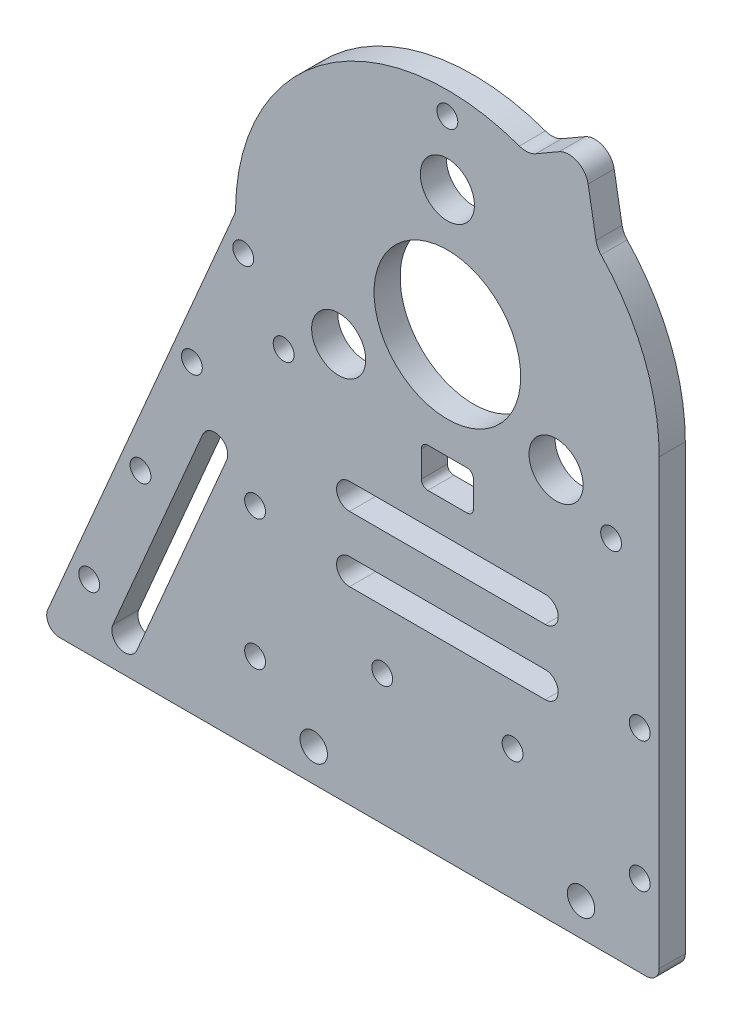
SolidWorks part; units mm, degrees
material "Thornel Mat VMA"
ref_plane "前视" through (0, 0, 0) normal (0, 0, 1) x (1, 0, 0)
ref_plane "上视" through (0, 0, 0) normal (0, 1, 0) x (1, 0, 0)
ref_plane "右视" through (0, 0, 0) normal (1, 0, 0) x (0, 0, -1)
sketch "草图1" plane through (0, 0, 0) normal (0, 0, 1) x (1, 0, 0)
  circle A0 centre (0, 0) radius 32.5
  circle A1 centre (0, 0) radius 11.25
  dimension "D1" = 22.5
  dimension "D2" = 65
extrude "凸台-拉伸1" add sketch "草图1" along normal blind 4
sketch "草图2" plane through (0, 0, 4) normal (0, 0, 1) x (1, 0, 0)
  line L0 (-32.5, 0) -> (-32.5, -70)
  line L1 (-32.5, -70) -> (32.5, -70)
  line L2 (32.5, -70) -> (32.5, 0)
  circle A0 centre (0, 0) radius 32.5 construction
  arc A1 (-32.5, 0) -> (32.5, 0) centre (0, 0) ccw
  dimension "D1" = 70
extrude "凸台-拉伸2" add sketch "草图2" against normal blind 4
sketch "草图3" plane through (0, 0, 4) normal (0, 0, 1) x (1, 0, 0)
  line L0 (0, 0) -> (0, 32.5) construction
  line L1 (0, 0) -> (0, 19.25) construction
  arc A0 (32.5, 0) -> (-32.5, 0) centre (0, 0) ccw construction
  circle A1 centre (0, 19.25) radius 4.15
  circle A2 centre (16.671, -9.625) radius 4.15
  circle A3 centre (-16.671, -9.625) radius 4.15
  dimension "D1" = 8.3
  dimension "D3" = 19.25
  dimension "D2" = 3
extrude "切除-拉伸1" cut sketch "草图3" against normal blind 4
sketch "草图4" plane through (0, 0, 4) normal (0, 0, 1) x (1, 0, 0)
  line L0 (0, 0) -> (0, 32.5) construction
  line L1 (0, 0) -> (0, 29) construction
  arc A0 (32.5, 0) -> (-32.5, 0) centre (0, 0) ccw construction
  circle A1 centre (0, 29) radius 1.6
  circle A2 centre (25.1147, -14.5) radius 1.6
  circle A3 centre (-25.1147, -14.5) radius 1.6
  dimension "D2" = 3.2
  dimension "D4" = 29
  dimension "D3" = 3
extrude "切除-拉伸2" cut sketch "草图4" against normal blind 4
sketch "草图5" plane through (0, 0, 4) normal (0, 0, 1) x (1, 0, 0)
  line L0 (0, 0) -> (0, -70) construction
  line L1 (-32.5, -70) -> (32.5, -70) construction
  line L2 (17.6, -70) -> (17.6, -74)
  line L3 (17.6, -70) -> (-17.6, -70)
  line L4 (0, -70) -> (0, -74)
  line L5 (17.6, -74) -> (-17.6, -74)
  line L6 (-17.6, -70) -> (-17.6, -74)
  line M14 (-32.5, -70) -> (32.5, -70)
  dimension "D1" = 4
  dimension "D2" = 17.6
extrude "凸台-拉伸3" add sketch "草图5" against normal blind 4 contours L6 L5 L4 M14 | L5 L2 L3 L4
sketch "草图6" plane through (0, 0, 4) normal (0, 0, 1) x (1, 0, 0)
  line L0 (0, 0) -> (0, -74) construction
  line L1 (17.6, -74) -> (-17.6, -74) construction
  line L2 (-32.5, -70) -> (-17.6, -70) construction
  line L3 (-20.5, -65) -> (20.5, -65) construction
  circle A0 centre (-20.5, -65) radius 2.1
  circle A1 centre (20.5, -65) radius 2.1
  dimension "D1" = 41
  dimension "D2" = 5
  dimension "D3" = 4.2
extrude "切除-拉伸3" cut sketch "草图6" against normal blind 4
sketch "草图7" plane through (0, 0, 4) normal (0, 0, 1) x (1, 0, 0)
  line L0 (0, 0) -> (0, -74) construction
  line L1 (17.6, -74) -> (-17.6, -74) construction
  line L3 (-4, -16.2) -> (4, -16.2)
  line L4 (-4, -16.2) -> (-4, -22.2)
  line L5 (-4, -22.2) -> (4, -22.2)
  line L6 (4, -16.2) -> (4, -22.2)
  line L7 (-4, -16.2) -> (4, -22.2) construction
  line L8 (-4, -22.2) -> (4, -16.2) construction
  point P5 (0, -19.2)
  dimension "D1" = 6
  dimension "D2" = 8
  dimension "D3" = 16.2
extrude "切除-拉伸4" cut sketch "草图7" against normal blind 4
fillet "圆角1" radius 1 4 edges at (4, -16.2, 2) (4, -22.2, 2) (-4, -22.2, 2) (-4, -16.2, 2)
sketch "草图8" plane through (0, 0, 0) normal (0, 0, -1) x (-1, 0, 0)
  line L0 (0, -74) -> (0, 0) construction
  line L1 (-17.6, -74) -> (17.6, -74) construction
  line L2 (-17.6, -70) -> (-32.5, -70) construction
  circle A0 centre (-10, -50) radius 1.6
  circle A1 centre (10, -50) radius 1.6
  dimension "D1" = 3.2
  dimension "D2" = 20
  dimension "D3" = 20
extrude "切除-拉伸5" cut sketch "草图8" against normal blind 10
sketch "草图9" plane through (0, 0, 4) normal (0, 0, 1) x (1, 0, 0)
  line L1 (-17.6, -74) -> (17.6, -74)
  line L2 (-17.6, -74) -> (-17.6, -70)
  line L3 (-17.6, -70) -> (17.6, -70)
  line L4 (17.6, -74) -> (17.6, -70)
extrude "切除-拉伸6" cut sketch "草图9" against normal blind 10
sketch "草图10" plane through (0, 0, 4) normal (0, 0, 1) x (1, 0, 0)
  line L0 (-29.5, -70) -> (-29.5, 44.9866) construction
  line L1 (-32.5, -70) -> (32.5, -70) construction
  line L2 (-32.5, 0) -> (-32.5, -70) construction
  line L3 (0, 32.5) -> (0, -70) construction
  circle A0 centre (-29.5, -57.5) radius 1.6
  circle A1 centre (-29.5, -37.5) radius 1.6
  arc A2 (32.5, 0) -> (-32.5, 0) centre (0, 0) ccw construction
  circle A3 centre (29.5, -37.5) radius 1.6
  circle A4 centre (29.5, -57.5) radius 1.6
  dimension "D2" = 3.2
  dimension "D3" = 12.5
  dimension "D4" = 20
  dimension "D1" = 3
extrude "切除-拉伸7" cut sketch "草图10" against normal blind 10
sketch "草图11" plane through (0, 0, 4) normal (0, 0, 1) x (1, 0, 0)
  line L0 (12.3168, 30.0757) -> (20.846, 35)
  line L1 (20.846, 35) -> (22.9619, 23)
  line L2 (-1000, 0) -> (49000, 0) construction
  arc A0 (32.5, 0) -> (-32.5, 0) centre (0, 0) ccw construction
  arc A1 (22.9619, 23) -> (12.3168, 30.0757) centre (0, 0) ccw
  dimension "D1" = 100
  dimension "D2" = 30
  dimension "D3" = 35
  dimension "D4" = 12
extrude "凸台-拉伸4" add sketch "草图11" against normal blind 4
fillet "圆角2" radius 3 3 edges at (12.3168, 30.0757, 2) (22.9619, 23, 2) (20.846, 35, 2)
sketch "草图12" plane through (0, 0, 4) normal (0, 0, 1) x (1, 0, 0)
  line L0 (-15, -29) -> (15, -29) construction
  line L1 (-15, -27) -> (15, -27)
  line L2 (-15, -31) -> (15, -31)
  line L3 (0, 0) -> (0, -29) construction
  line L4 (-15, -39) -> (15, -39) construction
  line L5 (-15, -37) -> (15, -37)
  line L6 (-15, -41) -> (15, -41)
  arc A0 (-15, -27) -> (-15, -31) centre (-15, -29) ccw
  arc A1 (15, -31) -> (15, -27) centre (15, -29) ccw
  circle A2 centre (0, 0) radius 11.25 construction
  arc A3 (-15, -37) -> (-15, -41) centre (-15, -39) ccw
  arc A4 (15, -41) -> (15, -37) centre (15, -39) ccw
  point P2 (0, -29)
  point P14 (0, -39)
  dimension "D2" = 2
  dimension "D4" = 2
  dimension "D1" = 30
  dimension "D3" = 27
  dimension "D5" = 30
  dimension "D6" = 6
extrude "切除-拉伸8" cut sketch "草图12" against normal blind 10
sketch "草图13" plane through (0, 0, 4) normal (0, 0, 1) x (1, 0, 0)
  line L0 (-32.5, 0) -> (-62.5, -70)
  line L1 (-62.5, -70) -> (-32.5, -70)
  line L2 (-32.5, -70) -> (-32.5, 0)
  line L3 (-32.5, -70) -> (32.5, -70) construction
  dimension "D1" = 30
extrude "凸台-拉伸5" add sketch "草图13" against normal blind 4
fillet "圆角3" radius 2 3 edges at (32.5, -70, 2) (-62.5, -70, 2) (-32.5, 0, 2)
sketch "草图14" plane through (0, 0, 4) normal (0, 0, 1) x (1, 0, 0)
  line L0 (-35.6903, -32.8299) -> (-49.4775, -65) construction
  line L1 (-33.852, -33.6178) -> (-47.6392, -65.7878)
  line L2 (-37.5286, -32.0421) -> (-51.3158, -64.2122)
  line L3 (-32.6592, -0.3715) -> (-61.3052, -67.2122) construction
  line L4 (-59.4669, -70) -> (30.5, -70) construction
  line L5 (-59.2426, -70.0152) -> (-33.578, -10.1312) construction
  arc A0 (-33.852, -33.6178) -> (-37.5286, -32.0421) centre (-35.6903, -32.8299) ccw
  arc A1 (-51.3158, -64.2122) -> (-47.6392, -65.7878) centre (-49.4775, -65) ccw
  circle A2 centre (-54.9504, -60) radius 1.6
  circle A3 centre (-47.072, -41.6171) radius 1.6
  circle A4 centre (-39.1936, -23.2342) radius 1.6
  circle A5 centre (-31.3152, -4.8513) radius 1.6
  point P2 (-42.5839, -48.915)
  dimension "D1" = 2
  dimension "D3" = 5
  dimension "D5" = 3.2
  dimension "D6" = 20
  dimension "D7" = 20
  dimension "D8" = 10
  dimension "D9" = 20
  dimension "D2" = 35
  dimension "D4" = 8
  dimension "D10" = 3
extrude "切除-拉伸9" cut sketch "草图14" against normal blind 10
